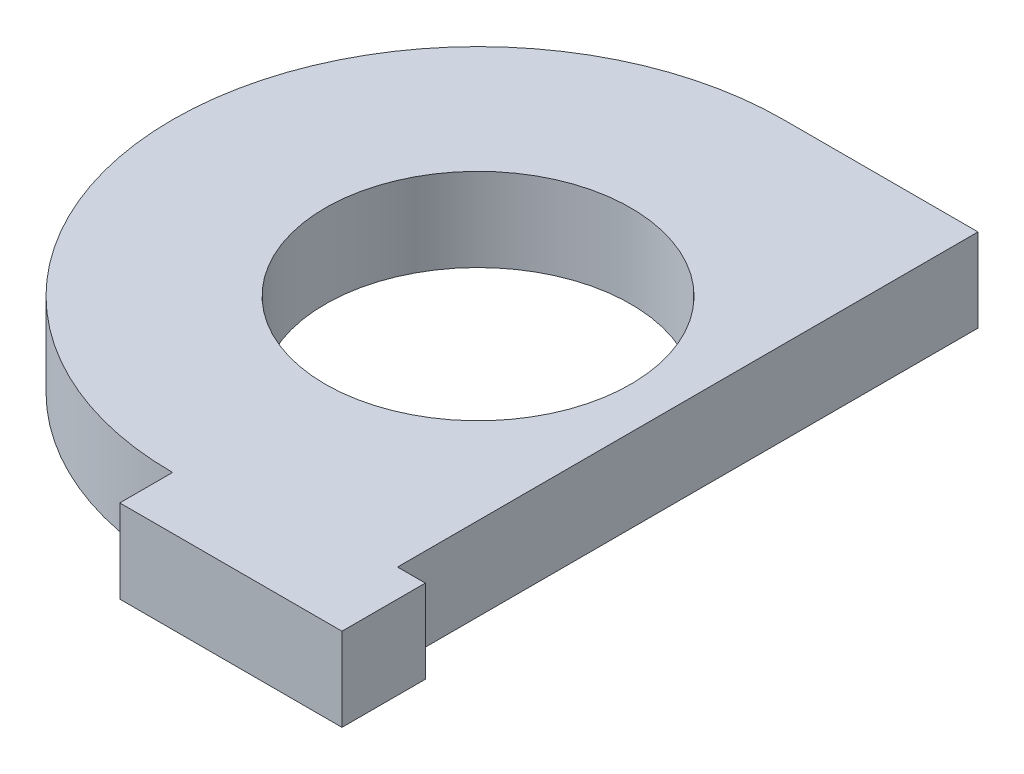
SolidWorks part; units mm, degrees
ref_plane "Front Plane" through (0, 0, 0) normal (0, 0, 1) x (1, 0, 0)
ref_plane "Top Plane" through (0, 0, 0) normal (0, 1, 0) x (1, 0, 0)
ref_plane "Right Plane" through (0, 0, 0) normal (1, 0, 0) x (0, 0, -1)
sketch "Sketch1" plane through (0, 0, 0) normal (0, 1, 0) x (1, 0, 0)
  line L0 (0, 0) -> (0, 41.8)
  line L1 (0, 41.8) -> (-14, 41.8)
  line L5 (-14, -2.2) -> (-14, -6)
  line L7 (-14, -6) -> (2, -6)
  line L9 (0, 0) -> (2, 0)
  line L12 (2, 0) -> (2, -6)
  arc A0 (-14, 41.8) -> (-14, -2.2) centre (-14, 19.8) ccw
  circle A1 centre (-14, 19.8) radius 11
  dimension "D3" = 22
  dimension "D4" = 22
  dimension "D1" = 19.8
  dimension "D2" = 14
  dimension "D5" = 6
  dimension "D6" = 16
extrude "Boss-Extrude1" add sketch "Sketch1" along normal blind 6
